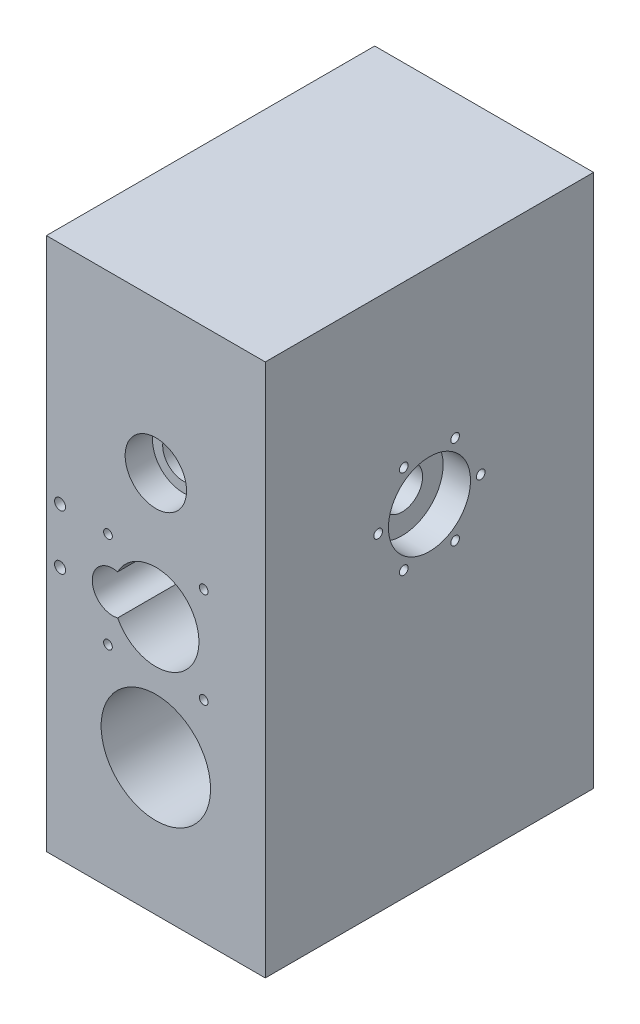
SolidWorks part; units mm, degrees
material "6061-T6 (SS)"
ref_plane "Front Plane" through (0, 0, 0) normal (0, 0, 1) x (1, 0, 0)
ref_plane "Top Plane" through (0, 0, 0) normal (0, 1, 0) x (1, 0, 0)
ref_plane "Right Plane" through (0, 0, 0) normal (1, 0, 0) x (0, 0, -1)
sketch "Sketch1" plane through (0, 0, 0) normal (0, 0, 1) x (1, 0, 0)
  line L1 (-50.8, -123.825) -> (50.8, -123.825)
  line L2 (-50.8, -123.825) -> (-50.8, 123.825)
  line L3 (-50.8, 123.825) -> (50.8, 123.825)
  line L4 (50.8, -123.825) -> (50.8, 123.825)
  line L5 (-50.8, -123.825) -> (50.8, 123.825) construction
  line L6 (-50.8, 123.825) -> (50.8, -123.825) construction
  point P0 (0, 0)
  dimension "D1" = 247.65
  dimension "D2" = 101.6
extrude "Boss-Extrude1" add sketch "Sketch1" along normal blind 152.4
sketch "Sketch2" plane through (0, 0, 0) normal (0, 0, -1) x (-1, 0, 0)
  line L2 (50.8, -123.825) -> (-50.8, -123.825) construction
  circle A0 centre (0, -60.579) radius 15.0813
  circle A1 centre (0, 53.721) radius 9.525
  dimension "D1" = 30.1625
  dimension "D2" = 63.246
  dimension "D3" = 19.05
  dimension "D4" = 114.3
extrude "Cut-Extrude1" cut sketch "Sketch2" against normal through all
sketch "Sketch3" plane through (-50.8, 0, 0) normal (-1, 0, 0) x (0, 0, 1)
  line L0 (152.4, -60.325) -> (88.9, -123.825)
  line L1 (152.4, 123.825) -> (152.4, -123.825) construction
  line L2 (152.4, -123.825) -> (0, -123.825) construction
  line L3 (88.9, -123.825) -> (152.4, -123.825)
  line L4 (152.4, -123.825) -> (152.4, -60.325)
  dimension "D2" = 63.5
sketch "Sketch4" plane through (50.8, 0, 0) normal (1, 0, 0) x (0, 0, -1)
  line L0 (-152.4, 123.825) -> (0, 123.825) construction
  line L1 (-152.4, -60.325) -> (-152.4, 123.825) construction
  circle A0 centre (-76.2, 28.575) radius 19.05
  dimension "D1" = 38.1
  dimension "D3" = 76.2
  dimension "D2" = 95.25
sketch "Sketch33" plane through (0, 0, 0) normal (0, 0, -1) x (-1, 0, 0)
  line L2 (-40.005, 102.9335) -> (40.005, 102.9335) construction
  line L3 (-40.005, 102.9335) -> (-40.005, 4.5085) construction
  line L4 (-40.005, 4.5085) -> (40.005, 4.5085) construction
  line L5 (40.005, 102.9335) -> (40.005, 4.5085) construction
  line L6 (-40.005, 102.9335) -> (40.005, 4.5085) construction
  line L8 (-40.005, 4.5085) -> (40.005, 102.9335) construction
  circle A0 centre (-40.005, 102.9335) radius 2.5797
  circle A1 centre (40.005, 102.9335) radius 2.5797
  circle A2 centre (40.005, 4.5085) radius 2.5797
  circle A3 centre (-40.005, 4.5085) radius 2.5797
  point P4 (0, 53.721)
  dimension "D1" = 98.425
  dimension "D3" = 5.1594
  dimension "D2" = 40.005
extrude "Cut-Extrude33" cut sketch "Sketch33" against normal blind 25.4
sketch "Sketch53" plane through (0, 0, 0) normal (0, 0, -1) x (-1, 0, 0)
  circle A0 centre (0, -60.579) radius 31.75
  dimension "D1" = 63.5
extrude "Cut-Extrude37" cut sketch "Sketch53" against normal blind 24.13
sketch "Sketch54" plane through (0, 0, 0) normal (0, 0, -1) x (-1, 0, 0)
  circle A0 centre (0, 53.721) radius 19.05
  dimension "D1" = 38.1
extrude "Cut-Extrude38" cut sketch "Sketch54" against normal blind 38.1
extrude "Cut-Extrude40" cut sketch "Sketch4" against normal blind 12.7
sketch "Sketch55" plane through (-50.8, 0, 0) normal (-1, 0, 0) x (0, 0, 1)
  line L0 (76.2, 28.575) -> (52.3875, 28.575) construction
  line L1 (76.2, 28.575) -> (64.2938, 49.1972) construction
  circle A0 centre (76.2, 28.575) radius 23.8125 construction
  circle A1 centre (52.3875, 28.575) radius 1.7859
  circle A2 centre (64.2938, 49.1972) radius 1.7859
  circle A3 centre (88.1063, 49.1972) radius 1.7859
  circle A4 centre (100.0125, 28.575) radius 1.7859
  circle A5 centre (88.1062, 7.9528) radius 1.7859
  circle A6 centre (64.2937, 7.9528) radius 1.7859
  dimension "D1" = 47.625
  dimension "D2" = 3.5719
  dimension "D4" = 60
  dimension "D5" = 23.8125
  dimension "D3" = 6
sketch "Sketch56" plane through (0, 0, 152.4) normal (0, 0, 1) x (1, 0, 0)
  circle A0 centre (0, 53.721) radius 14.2494
  dimension "D1" = 28.4988
extrude "Cut-Extrude42" cut sketch "Sketch56" against normal blind 12.7
sketch "Sketch57" plane through (0, 0, 38.1) normal (0, 0, -1) x (-1, 0, 0)
  circle A0 centre (0, 53.721) radius 14.2494
  dimension "D1" = 28.4988
extrude "Cut-Extrude43" cut sketch "Sketch57" against normal blind 12.7
sketch "Sketch58" plane through (0, 0, 152.4) normal (0, 0, 1) x (1, 0, 0)
  circle A0 centre (0, -60.579) radius 25.4
  dimension "D1" = 50.8
extrude "Cut-Extrude44" cut sketch "Sketch58" against normal blind 50.8
sketch "Sketch59" plane through (0, 0, 152.4) normal (0, 0, 1) x (1, 0, 0)
  line L1 (-22.225, 18.1356) -> (22.225, 18.1356) construction
  line L2 (-22.225, 18.1356) -> (-22.225, -26.3144) construction
  line L3 (-22.225, -26.3144) -> (22.225, -26.3144) construction
  line L4 (22.225, 18.1356) -> (22.225, -26.3144) construction
  line L5 (-22.225, 18.1356) -> (22.225, -26.3144) construction
  line L6 (-22.225, -26.3144) -> (22.225, 18.1356) construction
  arc A0 (-17.7346, -13.3405) -> (-17.7346, 5.1617) centre (0, -4.0894) ccw
  circle A1 centre (0, 53.721) radius 9.525 construction
  circle A2 centre (-22.225, 18.1356) radius 2.0193 construction
  circle A3 centre (22.225, 18.1356) radius 2.0193 construction
  circle A4 centre (22.225, -26.3144) radius 2.0193 construction
  circle A5 centre (-22.225, -26.3144) radius 2.0193 construction
  arc A6 (-17.7346, 5.1617) -> (-17.7346, -13.3405) centre (-20.0025, -4.0894) ccw
  dimension "D2" = 40.005
  dimension "D4" = 4.0386
  dimension "D5" = 19.05
  dimension "D1" = 57.8104
  dimension "D3" = 44.45
extrude "Cut-Extrude45" cut sketch "Sketch59" against normal blind 127
fillet "Fillet2" radius 0.0025 4 edges at (50.8, -123.825, 76.2) (-50.8, -123.825, 76.2) (50.8, 123.825, 76.2) (-50.8, 123.825, 76.2)
sketch "Sketch60" plane through (-50.8, 0, 0) normal (-1, 0, 0) x (0, 0, 1)
  line L0 (0, 123.825) -> (152.4, 123.825) construction
  line L1 (0, 123.8225) -> (0, -123.8225) construction
  circle A0 centre (76.2, 28.575) radius 19.05
  dimension "D3" = 38.1
  dimension "D1" = 95.25
  dimension "D2" = 76.2
extrude "Cut-Extrude46" cut sketch "Sketch60" against normal blind 12.7
sketch "Sketch61" plane through (50.8, 0, 0) normal (1, 0, 0) x (0, 0, -1)
  circle A0 centre (-76.2, 28.575) radius 9.525
  dimension "D1" = 19.05
extrude "Cut-Extrude47" cut sketch "Sketch61" against normal through all
sketch "Sketch62" plane through (0, 0, 152.4) normal (0, 0, 1) x (1, 0, 0)
  line L1 (-22.225, 18.1356) -> (22.225, 18.1356) construction
  line L2 (-22.225, 18.1356) -> (-22.225, -26.3144) construction
  line L3 (-22.225, -26.3144) -> (22.225, -26.3144) construction
  line L4 (22.225, 18.1356) -> (22.225, -26.3144) construction
  line L5 (-22.225, 18.1356) -> (22.225, -26.3144) construction
  line L6 (-22.225, -26.3144) -> (22.225, 18.1356) construction
  circle A0 centre (-22.225, 18.1356) radius 2.0193
  circle A1 centre (22.225, 18.1356) radius 2.0193
  circle A2 centre (22.225, -26.3144) radius 2.0193
  circle A3 centre (-22.225, -26.3144) radius 2.0193
  point P0 (0, -4.0894)
  dimension "D2" = 4.0386
  dimension "D1" = 44.45
hole_wizard "#10-32 Tapped Hole1" positions "Sketch63" profile "Sketch64" tap size "#10-32" standard "ANSI Inch"
sketch "Sketch63" plane through (0, 0, 152.4) normal (0, 0, 1) x (1, 0, 0)
  point P0 (-22.225, 18.1356)
  point P3 (22.225, 18.1356)
  point P6 (22.225, -26.3144)
  point P9 (-22.225, -26.3144)
sketch "Sketch64" plane through (-22.225, 18.1356, 152.4) normal (1, 0, 0) x (0, -1, 0)
  line L0 (0, 0) -> (0, 26.6133)
  line L1 (0, 26.6133) -> (2.0193, 25.4)
  line L2 (2.0193, 25.4) -> (2.0193, 0)
  line L5 (2.0193, 0) -> (0, 0)
  line L10 (0, 26.6133) -> (-2.0193, 25.4) construction
  line L11 (0, -6.35) -> (0, 107.95) construction
  dimension "Tap Drill Dia." = 4.0386
  dimension "Tap Drill Depth" = 25.4
  dimension "Drill Angle" = 118
cosmetic thread "Hole Thread1" parameters "D1"=9.652, "D2"=4.826
cosmetic thread "Hole Thread2" parameters "D1"=9.652, "D2"=4.826
cosmetic thread "Hole Thread3" parameters "D1"=9.652, "D2"=4.826
cosmetic thread "Hole Thread4" parameters "D1"=9.652, "D2"=4.826
hole_wizard "#10-32 Tapped Hole2" positions "Sketch65" profile "Sketch66" tap size "#10-32" standard "ANSI Inch"
sketch "Sketch65" plane through (-50.8, 0, 0) normal (-1, 0, 0) x (0, 0, 1)
  point P0 (64.2937, 7.9528)
  point P3 (52.3875, 28.575)
  point P6 (88.1062, 7.9528)
  point P9 (100.0125, 28.575)
  point P12 (88.1063, 49.1972)
  point P15 (64.2938, 49.1972)
sketch "Sketch66" plane through (-50.8, 7.9528, 64.2937) normal (0, 1, 0) x (0, 0, 1)
  line L0 (0, 0) -> (0, 26.6133)
  line L1 (0, 26.6133) -> (2.0193, 25.4)
  line L2 (2.0193, 25.4) -> (2.0193, 0)
  line L5 (2.0193, 0) -> (0, 0)
  line L10 (0, 26.6133) -> (-2.0193, 25.4) construction
  line L11 (0, -6.35) -> (0, 107.95) construction
  dimension "Tap Drill Dia." = 4.0386
  dimension "Tap Drill Depth" = 25.4
  dimension "Drill Angle" = 118
cosmetic thread "Hole Thread5" parameters "D1"=9.652, "D2"=4.826
cosmetic thread "Hole Thread6" parameters "D1"=9.652, "D2"=4.826
cosmetic thread "Hole Thread7" parameters "D1"=9.652, "D2"=4.826
cosmetic thread "Hole Thread8" parameters "D1"=9.652, "D2"=4.826
cosmetic thread "Hole Thread9" parameters "D1"=9.652, "D2"=4.826
cosmetic thread "Hole Thread10" parameters "D1"=9.652, "D2"=4.826
mirror "Mirror1" about plane through (0, 0, 0) normal (1, 0, 0) of "#10-32 Tapped Hole2"
sketch "Sketch67" plane through (0, 0, 152.4) normal (0, 0, 1) x (1, 0, 0)
  line L0 (50.7975, 123.825) -> (-50.7975, 123.825) construction
  line L1 (-50.8, 123.8225) -> (-50.8, -123.8225) construction
  point P0 (-44.45, 19.05)
  point P1 (-44.45, -6.35)
  dimension "D1" = 25.4
  dimension "D2" = 104.775
  dimension "D3" = 6.35
hole_wizard "1/4-20 Tapped Hole1" positions "Sketch68" profile "Sketch70" tap size "1/4-20" standard "ANSI Inch"
sketch "Sketch68" plane through (0, 0, 152.4) normal (0, 0, 1) x (1, 0, 0)
  point P0 (-44.45, 19.05)
  point P3 (-44.45, -6.35)
sketch "Sketch70" plane through (-44.45, 19.05, 152.4) normal (1, 0, 0) x (0, -1, 0)
  line L0 (0, 0) -> (0, 20.5838)
  line L1 (0, 20.5838) -> (2.5527, 19.05)
  line L2 (2.5527, 19.05) -> (2.5527, 0)
  line L5 (2.5527, 0) -> (0, 0)
  line L10 (0, 20.5838) -> (-2.5527, 19.05) construction
  line L11 (0, -6.35) -> (0, 107.95) construction
  dimension "Tap Drill Dia." = 5.1054
  dimension "Tap Drill Depth" = 19.05
  dimension "Drill Angle" = 118
cosmetic thread "Hole Thread11" parameters "D1"=12.7, "D2"=6.35
cosmetic thread "Hole Thread12" parameters "D1"=12.7, "D2"=6.35
